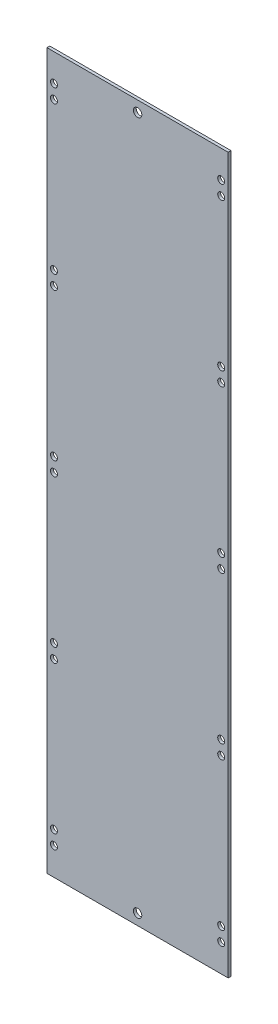
SolidWorks part; units mm, degrees
ref_plane "Front Plane" through (0, 0, 0) normal (0, 0, 1) x (1, 0, 0)
ref_plane "Top Plane" through (0, 0, 0) normal (0, 1, 0) x (1, 0, 0)
ref_plane "Right Plane" through (0, 0, 0) normal (1, 0, 0) x (0, 0, -1)
sketch "Sketch1" plane through (0, 0, 0) normal (0, 0, 1) x (1, 0, 0)
  line L1 (0, 0) -> (83, 0)
  line L2 (0, 0) -> (0, 327.5)
  line L3 (0, 327.5) -> (83, 327.5)
  line L4 (83, 0) -> (83, 327.5)
  dimension "D1" = 83
  dimension "D2" = 327.5
extrude "Boss-Extrude1" add sketch "Sketch1" along normal blind 1.3
sketch "Sketch2" plane through (0, 0, 1.3) normal (0, 0, 1) x (1, 0, 0)
  line L0 (0, 327.5) -> (0, 0) construction
  line L1 (83, 327.5) -> (0, 327.5) construction
  line L2 (0, 0) -> (83, 0) construction
  circle A0 centre (3.2, 314.9) radius 1.6
  circle A1 centre (3.2, 308.5) radius 1.6
  circle A2 centre (79.8, 314.9) radius 1.6
  circle A3 centre (79.8, 308.5) radius 1.6
  circle A4 centre (3.2, 240.925) radius 1.6
  circle A5 centre (3.2, 234.525) radius 1.6
  circle A6 centre (79.8, 240.925) radius 1.6
  circle A7 centre (79.8, 234.525) radius 1.6
  circle A8 centre (3.2, 166.95) radius 1.6
  circle A9 centre (3.2, 160.55) radius 1.6
  circle A10 centre (79.8, 166.95) radius 1.6
  circle A11 centre (79.8, 160.55) radius 1.6
  circle A12 centre (3.2, 92.975) radius 1.6
  circle A13 centre (3.2, 86.575) radius 1.6
  circle A14 centre (79.8, 92.975) radius 1.6
  circle A15 centre (79.8, 86.575) radius 1.6
  circle A16 centre (3.2, 19) radius 1.6
  circle A17 centre (3.2, 12.6) radius 1.6
  circle A18 centre (79.8, 19) radius 1.6
  circle A19 centre (79.8, 12.6) radius 1.6
  dimension "D1" = 3.2
  dimension "D4" = 3.2
  dimension "D2" = 3.2
  dimension "D3" = 12.6
  dimension "D5" = 6.4
  dimension "D6" = 3.2
  dimension "D9" = 12.6
  dimension "D7" = 2
  dimension "D8" = 5
extrude "Cut-Extrude1" cut sketch "Sketch2" against normal blind 1.3
sketch "Sketch3" plane through (0, 0, 1.3) normal (0, 0, 1) x (1, 0, 0)
  line L0 (83, 327.5) -> (0, 327.5) construction
  line L1 (0, 327.5) -> (0, 0) construction
  line L2 (83, 0) -> (83, 327.5) construction
  line L3 (0, 0) -> (83, 0) construction
  circle A0 centre (41.5, 322.524) radius 1.93
  circle A1 centre (41.5, 4.976) radius 1.93
  dimension "D1" = 3.86
  dimension "D5" = 3.86
  dimension "D2" = 4.976
  dimension "D3" = 41.5
  dimension "D4" = 41.5
  dimension "D6" = 41.5
  dimension "D7" = 41.5
  dimension "D8" = 4.976
extrude "Cut-Extrude2" cut sketch "Sketch3" against normal blind 1.3
